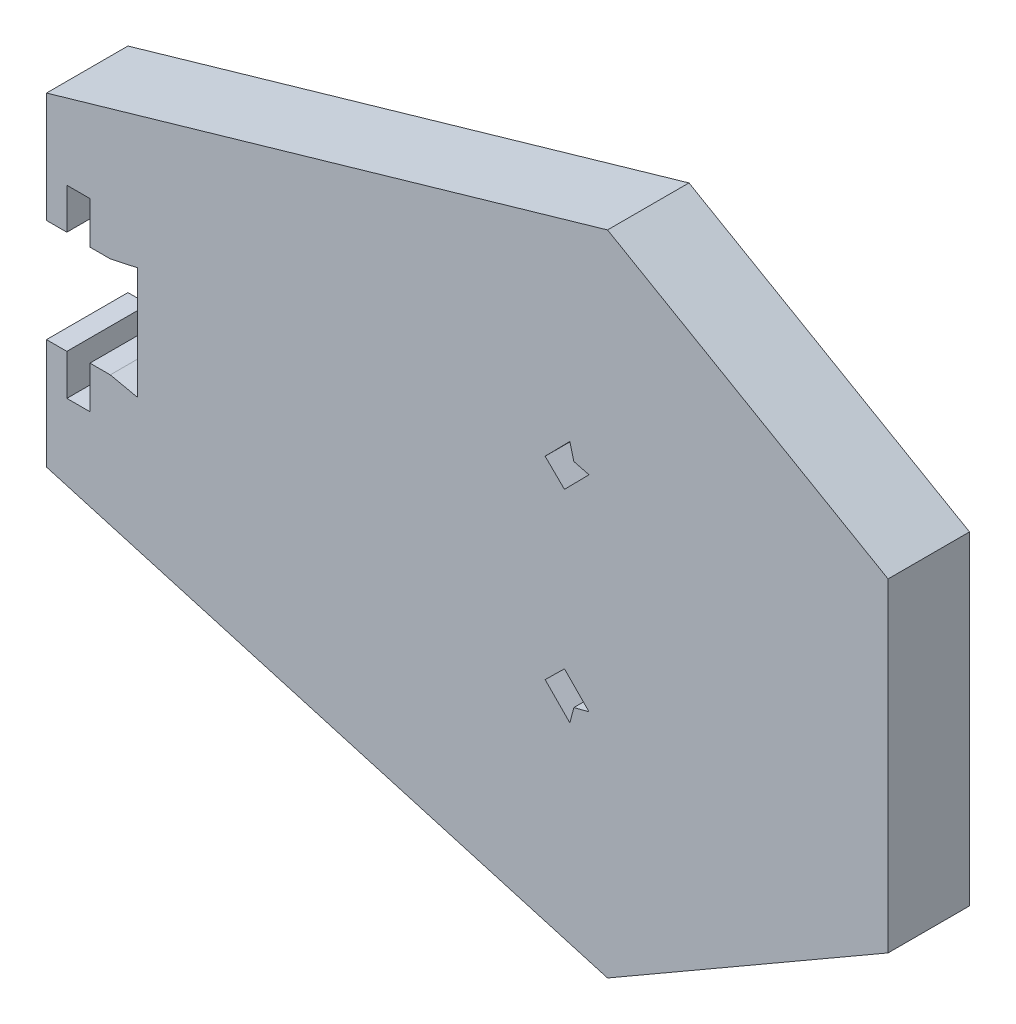
SolidWorks part; units mm, degrees
ref_plane "Front Plane" through (0, 0, 0) normal (0, 0, 1) x (1, 0, 0)
ref_plane "Top Plane" through (0, 0, 0) normal (0, 1, 0) x (1, 0, 0)
ref_plane "Right Plane" through (0, 0, 0) normal (1, 0, 0) x (0, 0, -1)
sketch "Sketch1" plane through (0, 0, 0) normal (0, 0, 1) x (1, 0, 0)
  line L0 (25.85, 11.9319) -> (5.1833, 23.8638) construction
  line L1 (25.85, -11.9319) -> (25.85, 11.9319) construction
  line L2 (5.1833, -23.8638) -> (25.85, -11.9319) construction
  line L3 (5.1833, -23.8638) -> (-36.15, -11.9319) construction
  line L4 (-36.15, 11.9319) -> (-36.15, -11.9319) construction
  line L5 (-36.15, 11.9319) -> (5.1833, 23.8638) construction
  line L6 (25.85, 11.9319) -> (5.1833, 23.8638)
  line L7 (25.85, -11.9319) -> (25.85, 11.9319)
  line L8 (5.1833, -23.8638) -> (25.85, -11.9319)
  line L9 (5.1833, -23.8638) -> (-36.15, -11.9319)
  line L10 (-36.15, 11.9319) -> (-36.15, -11.9319)
  line L11 (-36.15, 11.9319) -> (5.1833, 23.8638)
  line L18 (-36.15, 3.7) -> (-31.45, 3.7)
  line L19 (-31.45, 3.7) -> (-29.45, 4.1321)
  line L20 (-16.8732, 6.8495) -> (-31.45, 3.7) construction
  line L21 (-29.45, 4.1321) -> (-29.45, -4.1321)
  line L23 (-16.8732, -6.8495) -> (-31.45, -3.7) construction
  line L24 (-29.45, -4.1321) -> (-31.45, -3.7)
  line L25 (-31.45, -3.7) -> (-36.15, -3.7)
  line L26 (-34.55, 3.7) -> (-32.95, 3.7) construction
  line L27 (-31.45, 3.7) -> (-31.45, 1.4) construction
  line L28 (-36.15, 0) -> (25.85, 0) construction
  line L29 (2.4087, -8.9791) -> (0.5844, -7.1276)
  line L30 (0.5844, -7.1276) -> (2.009, -5.7239)
  line L31 (2.009, -5.7239) -> (3.8193, -7.5613)
  line L32 (3.8193, -7.5613) -> (2.7004, -7.8504)
  line L33 (2.7004, 7.8504) -> (2.4087, 8.9791)
  line L34 (2.7004, 7.8504) -> (2.4087, 8.9791)
  line L35 (3.8193, 7.5613) -> (2.7004, 7.8504)
  line L36 (3.8193, 7.5613) -> (2.7004, 7.8504)
  line L37 (2.009, 5.7239) -> (3.8193, 7.5613)
  line L38 (2.009, 5.7239) -> (3.8193, 7.5613)
  line L39 (0.5844, 7.1276) -> (2.009, 5.7239)
  line L40 (0.5844, 7.1276) -> (2.009, 5.7239)
  line L41 (2.4087, 8.9791) -> (0.5844, 7.1276)
  line L42 (2.4087, 8.9791) -> (0.5844, 7.1276)
  line L43 (2.7004, -7.8504) -> (2.4087, -8.9791)
  dimension "D1" = 2
  dimension "D2" = 0
extrude "Boss-Extrude1" add sketch "Sketch1" along normal blind 6
sketch "Sketch2" plane through (0, 0, 6) normal (0, 0, 1) x (1, 0, 0)
  line L20 (-36.25, -3.4275) -> (-36.25, -3.8)
  line L21 (-36.25, -3.8) -> (-34.65, -3.8)
  line L22 (-34.65, -3.8) -> (-34.65, -6.8)
  line L23 (-34.65, -6.8) -> (-32.95, -6.8)
  line L24 (-32.95, -6.8) -> (-32.95, 6.8)
  line L25 (-32.95, 6.8) -> (-34.65, 6.8)
  line L26 (-34.65, 6.8) -> (-34.65, 3.8)
  line L27 (-34.65, 3.8) -> (-36.25, 3.8)
  line L28 (-36.25, 3.8) -> (-36.25, 3.4275)
  line L29 (-36.25, 3.4275) -> (-36.25, -3.4275)
  line L30 (-36.25, -3.4275) -> (-36.25, -3.8)
  line L31 (-36.25, -3.8) -> (-34.65, -3.8)
  line L32 (-34.65, -3.8) -> (-34.65, -6.8)
  line L33 (-34.65, -6.8) -> (-32.95, -6.8)
  line L34 (-32.95, -6.8) -> (-32.95, 6.8)
  line L35 (-32.95, 6.8) -> (-34.65, 6.8)
  line L36 (-34.65, 6.8) -> (-34.65, 3.8)
  line L37 (-34.65, 3.8) -> (-36.25, 3.8)
  line L38 (-36.25, 3.8) -> (-36.25, 3.4275)
  line L39 (-36.25, 3.4275) -> (-36.25, -3.4275)
  dimension "D1" = 0.1
extrude "Cut-Extrude1" cut sketch "Sketch2" against normal through all
sketch "Sketch3" plane through (0, 0, 6) normal (0, 0, 1) x (1, 0, 0)
  line L0 (5.1833, 23.8638) -> (5.1833, -23.8638) construction
  line L1 (25.85, 0) -> (5.1833, 0) construction
  line L2 (25.85, -11.9319) -> (25.85, 11.9319) construction
ref_plane "Plane1" through (0, 0, 0) normal (0, 1, 0) x (-1, 0, 0)
